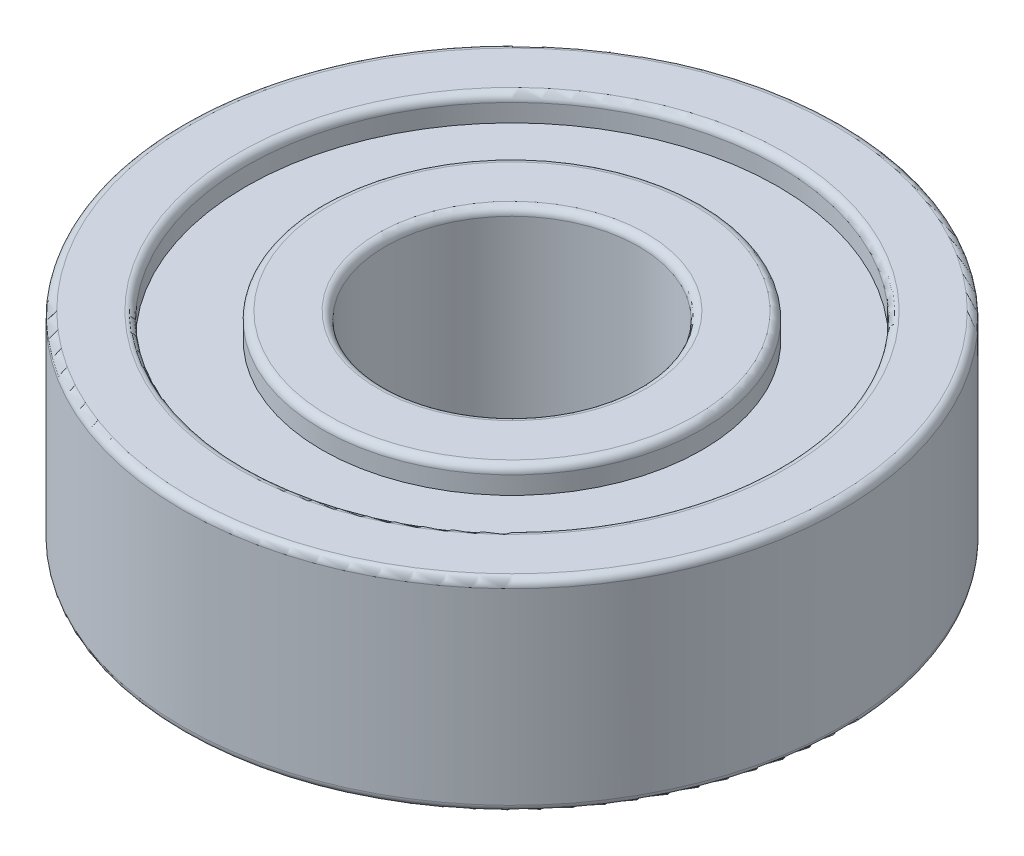
SolidWorks part; units mm, degrees
ref_plane "前视基准面" through (0, 0, 0) normal (0, 0, 1) x (1, 0, 0)
ref_plane "上视基准面" through (0, 0, 0) normal (0, 1, 0) x (1, 0, 0)
ref_plane "右视基准面" through (0, 0, 0) normal (1, 0, 0) x (0, 0, -1)
other "Configuration Table"
sketch "草图1" plane through (0, 0, 0) normal (0, 0, 1) x (1, 0, 0)
  line L0 (0, 4.6113) -> (0, -3.0029) construction
  line L1 (5, 8) -> (5, 0)
  line L2 (5, 0) -> (7.5, 0)
  line L3 (7.5, 0) -> (7.5, 1)
  line L4 (7.5, 1) -> (10.5, 1)
  line L5 (10.5, 1) -> (10.5, 0)
  line L6 (10.5, 0) -> (13, 0)
  line L7 (13, 0) -> (13, 8)
  line L8 (13, 8) -> (10.5, 8)
  line L9 (10.5, 8) -> (10.5, 7)
  line L10 (10.5, 7) -> (7.5, 7)
  line L11 (7.5, 7) -> (7.5, 8)
  line L12 (7.5, 8) -> (5, 8)
  dimension "D1" = 5
  dimension "D2" = 13
  dimension "D3" = 8
  dimension "D4" = 2.5
  dimension "D5" = 2.5
  dimension "D6" = 1
  dimension "D7" = 1
revolve "旋转1" add sketch "草图1" angle 360 about L0
fillet "圆角1" radius 0.3 8 edges at (0, 0, 5) (0, 0, 7.5) (0, 0, 10.5) (0, 0, 13) (0, 8, 7.5) (0, 8, 5) (0, 8, 13) (0, 8, 10.5)
